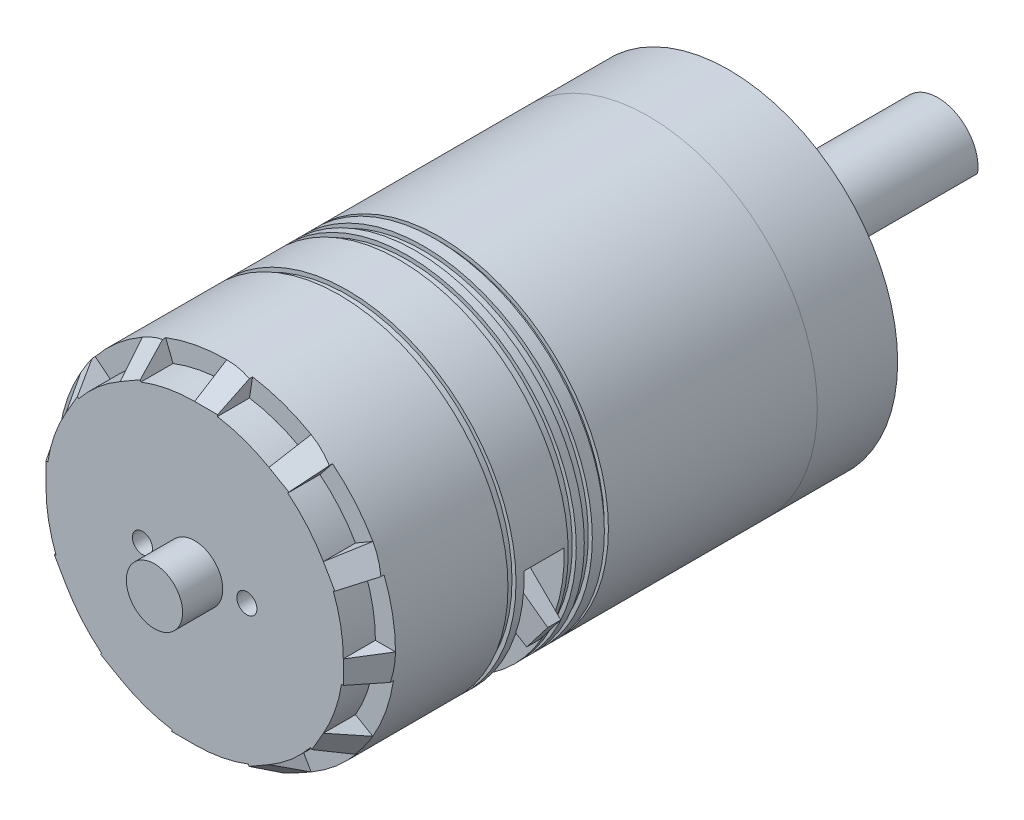
SolidWorks part; units mm, degrees
ref_plane "前视基准面" through (0, 0, 0) normal (0, 0, 1) x (1, 0, 0)
ref_plane "上视基准面" through (0, 0, 0) normal (0, 1, 0) x (1, 0, 0)
ref_plane "右视基准面" through (0, 0, 0) normal (1, 0, 0) x (0, 0, -1)
sketch "草图1" plane through (0, 0, 0) normal (0, 0, 1) x (1, 0, 0)
  circle A0 centre (0, 0) radius 21
  dimension "D1" = 42
extrude "凸台-拉伸1" add sketch "草图1" along normal blind 66.5
sketch "草图2" plane through (0, 0, 0) normal (0, 0, -1) x (-1, 0, 0)
  circle A0 centre (0, 0) radius 13
  dimension "D1" = 26
extrude "凸台-拉伸2" add sketch "草图2" along normal blind 2
sketch "草图3" plane through (0, 0, -2) normal (0, 0, -1) x (-1, 0, 0)
  circle A0 centre (0, 0) radius 5
  dimension "D1" = 10
extrude "凸台-拉伸3" add sketch "草图3" along normal blind 24
sketch "草图4" plane through (0, 0, -26) normal (0, 0, -1) x (-1, 0, 0)
  line L0 (-0.7071, -4.9497) -> (-4.9497, -0.7071)
  line L1 (0, 0) -> (0, -5) construction
  circle A0 centre (0, 0) radius 5 construction
  circle A1 centre (0, 0) radius 5 construction
  dimension "D1" = 4
  dimension "D2" = 45
extrude "切除-拉伸1" cut sketch "草图4" against normal blind 19.5 and the other way through all
hole_wizard "#8-36 螺纹孔1" positions "草图11" profile "草图12" tap size "#8-36" standard "ANSI Inch"
sketch "草图11" plane through (0, 0, 0) normal (0, 0, -1) x (-1, 0, 0)
  line L0 (0, 17.5) -> (0, 0) construction
  point P0 (0, 17.5)
  dimension "D1" = 17.5
sketch "草图12" plane through (0, 17.5, 0) normal (1, 0, 0) x (0, 1, 0)
  line L0 (0, 0) -> (0, 11.6517)
  line L1 (0, 11.6517) -> (2, 10.45)
  line L2 (2, 10.45) -> (2, 0)
  line L5 (2, 0) -> (0, 0)
  line L10 (0, 11.6517) -> (-2, 10.45) construction
  line L11 (0, -6.35) -> (0, 107.95) construction
  dimension "螺纹孔钻头直径" = 4
  dimension "螺纹孔钻头深度" = 10.45
  dimension "导头角度" = 118
cosmetic thread "孔螺蚊线1" parameters "D1"=8.33, "D2"=4.1656
chamfer "倒角1" distance 0.5 angle 45 1 edges at (-2, 17.5, 0)
pattern_circular "阵列(圆周)1" count 4 over 360 about axis through (0, 0, 0) along (0, 0, 1) of "#8-36 螺纹孔1", "倒角1"
sketch "草图13" plane through (0, 0, 0) normal (0, 0, -1) x (-1, 0, 0)
  line L0 (0, 21) -> (0, -21) construction
  line L1 (21, 0) -> (-21, 0) construction
  line L2 (0, 0) -> (14.8492, -14.8492) construction
  circle A0 centre (0, 0) radius 21 construction
  circle A1 centre (12.3744, -12.3744) radius 3
  circle A2 centre (12.3744, 12.3744) radius 3
  circle A3 centre (-12.3744, -12.3744) radius 3
  circle A4 centre (-12.3744, 12.3744) radius 3
  dimension "D1" = 45
  dimension "D2" = 17.5
  dimension "D3" = 6
sketch "草图30" plane through (0, 0, 66.5) normal (0, 0, 1) x (1, 0, 0)
  circle A0 centre (0, 0) radius 3.5
  dimension "D1" = 7
extrude "凸台-拉伸4" add sketch "草图30" along normal blind 5
sketch "草图31" plane through (0, 0, -2) normal (0, 0, -1) x (-1, 0, 0)
  circle A0 centre (0, 0) radius 8.25
  dimension "D1" = 16.5
extrude "凸台-拉伸5" add sketch "草图31" along normal blind 1
sketch "草图34" plane through (0, 0, 0) normal (0, 0, -1) x (-1, 0, 0)
  circle A0 centre (0, 0) radius 21
sketch3d "3D草图5"
  line L0 (0, 0, 0) -> (0, 0, 67.985)
  line L1 (21.6986, 0, 41.5) -> (15.6924, 6.0062, 41.5)
  line L3 (0, -21.6986, 41.5) -> (-6.0062, -15.6924, 41.5)
  line L4 (0, 0, -1.515) -> (0, 0, -26)
  line L5 (-6.0062, -15.6924, 41.5) -> (15.6924, 6.0062, 41.5)
  circle A1 centre (0, 0, 0) radius 21 construction
  arc A2 (0.7071, -4.9497, -26) -> (4.9497, -0.7071, -26) centre (0, 0, -26) ccw construction
  arc A5 (0, -21.6986, 41.5) -> (21.6986, 0, 41.5) centre (0, 0, 41.5) cw
  point P7 (0, 0, 21)
  point P15 (0, 0, -31)
  point P19 (0, 0, 63.1986)
  dimension "D2" = 41.5
  dimension "D1" = 41.5
extrude "切除-拉伸4" cut sketch "3D草图5" along a picked direction on the side against the normal blind 5 contours A5 L1 L5 L3
ref_plane "基准面1" through (0, 0, 48.5) normal (0, 0, 1) x (1, 0, 0)
sketch "草图38" plane through (0, 0, 48.5) normal (0, 0, 1) x (1, 0, 0)
  circle A0 centre (0, 0) radius 21 construction
  circle A1 centre (0, 0) radius 20.5
  circle A2 centre (0, 0) radius 21
  dimension "D1" = 41
extrude "切除-拉伸8" cut sketch "草图38" against normal blind 1
sketch "草图35" plane through (0, 0, 46.5) normal (0, 0, -1) x (-1, 0, 0)
  line L0 (-19.6508, 0.7225) -> (-13.5583, -7.2165)
  line L2 (-13.5583, -7.2165) -> (-10.385, -4.7813)
  line L3 (-10.385, -4.7813) -> (-16.6046, 3.3233)
  line L4 (-16.6046, 3.3233) -> (-19.6508, 0.9856)
  line L5 (-19.6508, 0.9856) -> (-19.6508, 0.7225)
extrude "凸台-拉伸8" add sketch "草图35" along normal blind 5
sketch "草图36" plane through (0, 0, 46.5) normal (0, 0, -1) x (-1, 0, 0)
  line L0 (0, -18.9231) -> (-7.5875, -12.4092)
  line L1 (-7.5875, -12.4092) -> (-4.982, -9.3742)
  line L2 (-4.982, -9.3742) -> (2.6055, -15.8881)
  line L3 (2.6055, -15.8881) -> (0, -18.9231)
extrude "凸台-拉伸9" add sketch "草图36" along normal blind 5
sketch "草图37" plane through (12.0185, -9.2231, 0) normal (0.7933, -0.6088, 0) x (0, 0, -1)
  line L0 (-41.5, 12.5367) -> (-46.5, 12.5367) construction
  line L1 (-43.367, 10.1324) -> (-45.6261, 10.1324)
  line L2 (-43.367, 10.1324) -> (-43.367, 5.2258)
  line L3 (-43.367, 5.2258) -> (-45.6261, 5.2258)
  line L4 (-45.6261, 10.1324) -> (-45.6261, 5.2258)
  line L5 (-46.5, 12.5367) -> (-46.5, 2.5293) construction
  dimension "D1" = 2.259
  dimension "D2" = 4.9065
  dimension "D3" = 2.4043
  dimension "D4" = 0.8739
extrude "凸台-拉伸10" add sketch "草图37" along normal blind 6 draft 3
ref_plane "基准面2" through (0, 0, 36) normal (0, 0, -1) x (-1, 0, 0)
sketch "草图39" plane through (0, 0, 36) normal (0, 0, -1) x (-1, 0, 0)
  circle A0 centre (0, 0) radius 21
  circle A1 centre (0, 0) radius 20.5
  dimension "D1" = 41
  dimension "D2" = 0.5
extrude "切除-拉伸9" cut sketch "草图39" against normal blind 0.5
ref_plane "基准面3" through (0, 0, 38) normal (0, 0, -1) x (-1, 0, 0)
sketch "草图41" plane through (0, 0, 38) normal (0, 0, -1) x (-1, 0, 0)
  circle A0 centre (0, 0) radius 21
  circle A1 centre (0, 0) radius 20.5
  dimension "D1" = 41
  dimension "D2" = 42
extrude "切除-拉伸10" cut sketch "草图41" against normal blind 1
ref_plane "基准面4" through (0, 0, 40) normal (0, 0, -1) x (-1, 0, 0)
sketch "草图42" plane through (0, 0, 40) normal (0, 0, -1) x (-1, 0, 0)
  circle A0 centre (0, 0) radius 21
  circle A1 centre (0, 0) radius 20.5
  dimension "D1" = 41
  dimension "D2" = 42
extrude "切除-拉伸11" cut sketch "草图42" against normal blind 1
ref_plane "基准面5" through (0, 0, 62.5) normal (0, 0, 1) x (1, 0, 0)
sketch "草图43" plane through (0, 0, 62.5) normal (0, 0, 1) x (1, 0, 0)
  line L0 (0, 18.5) -> (0, 21)
  line L1 (0, 0) -> (-10.5, 18.1865) construction
  line L2 (-6.6932, 17.2468) -> (-7.5977, 19.5774)
  arc A0 (0, 21) -> (-7.5977, 19.5774) centre (0, 0) ccw
  arc A1 (0, 18.5) -> (-6.6932, 17.2468) centre (0, 0) ccw
  dimension "D1" = 30
  dimension "D2" = 21
  dimension "D3" = 37
  dimension "D4" = 8.79
extrude "切除-拉伸12" cut sketch "草图43" along normal up to next
pattern_circular "阵列(圆周)4" count 12 over 360 about axis through (0, 0, 0) along (0, 0, 1) of "切除-拉伸12"
ref_plane "基准面6" through (0, 0, 0) normal (-0.866, -0.5, 0) x (0, 0, 1)
sketch "草图45" plane through (0, 0, 0) normal (-0.866, -0.5, 0) x (0, 0, 1)
  line L0 (62.5, 21) -> (66.5, 18.5)
  line L1 (66.5, 18.5) -> (66.5, 21)
  line L2 (66.5, 21) -> (62.5, 21)
extrude "切除-拉伸13" cut sketch "草图45" against normal up to next
pattern_circular "阵列(圆周)5" count 12 over 360 about axis through (0, 0, 0) along (0, 0, 1) of "切除-拉伸13"
sketch "草图48" plane through (0, 0, 0) normal (0, 1, 0) x (1, 0, 0)
  line L0 (21, -10) -> (-21, -10)
  line L1 (21, -36) -> (21, 0) construction
  line L2 (-21, 0) -> (-21, -36) construction
  line L3 (21, 0) -> (-21, 0) construction
  dimension "D1" = 10
split line "分割线2"
hole_wizard "M3 螺纹孔1" positions "草图50" profile "草图49" tap size "M3" standard "GB"
sketch "草图50" plane through (0, 0, 66.5) normal (0, 0, 1) x (1, 0, 0)
  line L0 (-6.5, 0) -> (0, 0) construction
  line L1 (0, 0) -> (0, 3.5) construction
  circle A0 centre (0, 0) radius 3.5 construction
  point P0 (-6.5, 0)
  point P14 (6.5, 0)
  dimension "D1" = 13
sketch "草图49" plane through (-6.5, 0, 66.5) normal (1, 0, 0) x (0, -1, 0)
  line L0 (0, 0) -> (0, 6.7511)
  line L1 (0, 6.7511) -> (1.25, 6)
  line L2 (1.25, 6) -> (1.25, 0)
  line L5 (1.25, 0) -> (0, 0)
  line L10 (0, 6.7511) -> (-1.25, 6) construction
  line L11 (0, -6.35) -> (0, 107.95) construction
  dimension "螺纹孔钻头直径" = 2.5
  dimension "螺纹孔钻头深度" = 6
  dimension "导头角度" = 118
cosmetic thread "孔螺蚊线2" parameters "D1"=4, "D2"=3
cosmetic thread "孔螺蚊线3" parameters "D1"=4, "D2"=3
extrude "切除-拉伸14" cut sketch "草图13" against normal blind 3
sketch "草图52" plane through (0, 0, 3) normal (0, 0, -1) x (-1, 0, 0)
  line L0 (0, 21) -> (0, 0) construction
  line L1 (13.8177, 12.3744) -> (13.0961, 13.6244)
  line L2 (13.0961, 13.6244) -> (11.6527, 13.6244)
  line L3 (11.6527, 13.6244) -> (10.931, 12.3744)
  line L4 (10.931, 12.3744) -> (11.6527, 11.1244)
  line L5 (11.6527, 11.1244) -> (13.0961, 11.1244)
  line L6 (13.0961, 11.1244) -> (13.8177, 12.3744)
  line L7 (0, 0) -> (-21, 0) construction
  line L8 (-13.0961, 11.1244) -> (-13.8177, 12.3744)
  line L9 (-11.6527, 11.1244) -> (-13.0961, 11.1244)
  line L10 (-10.931, 12.3744) -> (-11.6527, 11.1244)
  line L11 (-11.6527, 13.6244) -> (-10.931, 12.3744)
  line L12 (-13.0961, 13.6244) -> (-11.6527, 13.6244)
  line L13 (-13.8177, 12.3744) -> (-13.0961, 13.6244)
  line L14 (-13.8177, -12.3744) -> (-13.0961, -13.6244)
  line L15 (-13.0961, -13.6244) -> (-11.6527, -13.6244)
  line L16 (-11.6527, -13.6244) -> (-10.931, -12.3744)
  line L17 (-10.931, -12.3744) -> (-11.6527, -11.1244)
  line L18 (-11.6527, -11.1244) -> (-13.0961, -11.1244)
  line L19 (-13.0961, -11.1244) -> (-13.8177, -12.3744)
  line L20 (13.0961, -11.1244) -> (13.8177, -12.3744)
  line L21 (11.6527, -11.1244) -> (13.0961, -11.1244)
  line L22 (10.931, -12.3744) -> (11.6527, -11.1244)
  line L23 (11.6527, -13.6244) -> (10.931, -12.3744)
  line L24 (13.0961, -13.6244) -> (11.6527, -13.6244)
  line L25 (13.8177, -12.3744) -> (13.0961, -13.6244)
  circle A0 centre (12.3744, 12.3744) radius 1.25 construction
  circle A1 centre (-12.3744, 12.3744) radius 1.25 construction
  circle A2 centre (-12.3744, -12.3744) radius 1.25 construction
  circle A3 centre (12.3744, -12.3744) radius 1.25 construction
  dimension "D1" = 2.5
extrude "切除-拉伸15" cut sketch "草图52" against normal blind 1
